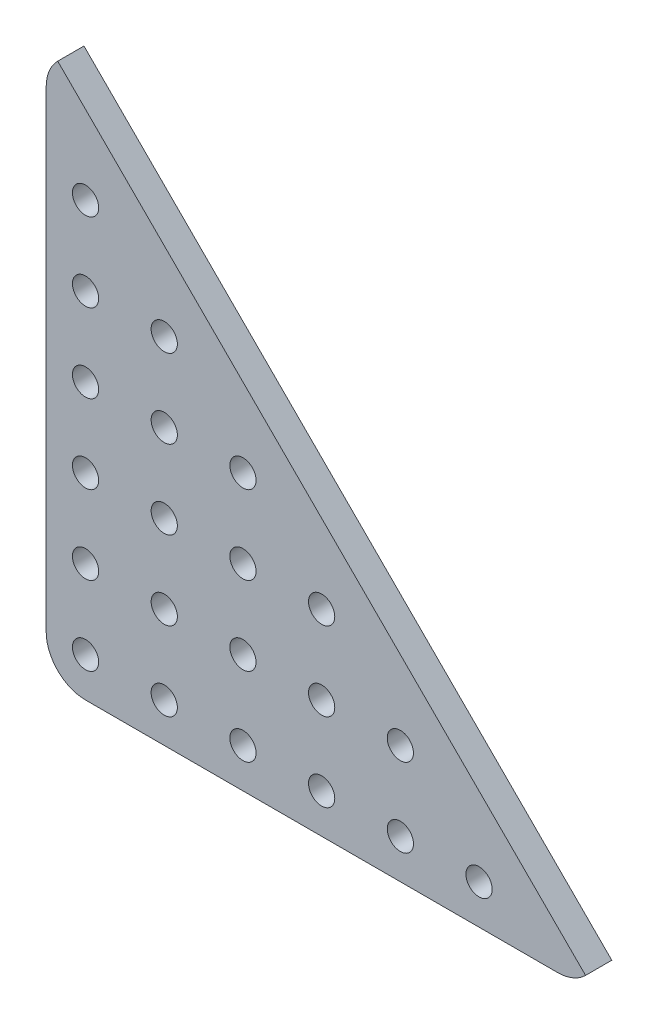
SolidWorks part; units mm, degrees
ref_plane "Alzado" through (0, 0, 0) normal (0, 0, 1) x (1, 0, 0)
ref_plane "Planta" through (0, 0, 0) normal (0, 1, 0) x (1, 0, 0)
ref_plane "Vista lateral" through (0, 0, 0) normal (1, 0, 0) x (0, 0, -1)
sketch "Model" plane through (0, 0, 0) normal (0, 0, 1) x (1, 0, 0)
  line L0 (-105.9434, 101.0565) -> (-105.9434, 47.0565)
  line L1 (-101.4434, 42.5565) -> (-47.4434, 42.5565)
  line L2 (-104.6254, 104.2385) -> (-44.2614, 43.8746)
  circle A0 centre (-101.4434, 92.0565) radius 1.5
  circle A1 centre (-101.4434, 83.0565) radius 1.5
  circle A2 centre (-92.4434, 83.0565) radius 1.5
  arc A3 (-104.6254, 104.2385) -> (-105.9434, 101.0565) centre (-101.4434, 101.0565) ccw
  arc A4 (-105.9434, 47.0565) -> (-101.4434, 42.5565) centre (-101.4434, 47.0565) ccw
  arc A5 (-47.4434, 42.5565) -> (-44.2614, 43.8746) centre (-47.4434, 47.0565) ccw
  circle A6 centre (-101.4434, 74.0565) radius 1.5
  circle A7 centre (-92.4434, 74.0565) radius 1.5
  circle A8 centre (-83.4434, 74.0565) radius 1.5
  circle A9 centre (-101.4434, 65.0565) radius 1.5
  circle A10 centre (-92.4434, 65.0565) radius 1.5
  circle A11 centre (-83.4434, 65.0565) radius 1.5
  circle A12 centre (-74.4434, 65.0565) radius 1.5
  circle A13 centre (-101.4434, 56.0565) radius 1.5
  circle A14 centre (-92.4434, 56.0565) radius 1.5
  circle A15 centre (-83.4434, 56.0565) radius 1.5
  circle A16 centre (-74.4434, 56.0565) radius 1.5
  circle A17 centre (-65.4434, 56.0565) radius 1.5
  circle A18 centre (-101.4434, 47.0565) radius 1.5
  circle A19 centre (-92.4434, 47.0565) radius 1.5
  circle A20 centre (-83.4434, 47.0565) radius 1.5
  circle A21 centre (-74.4434, 47.0565) radius 1.5
  circle A22 centre (-65.4434, 47.0565) radius 1.5
  circle A23 centre (-56.4434, 47.0565) radius 1.5
extrude "Saliente-Extruir1" add sketch "Model" along normal blind 3
